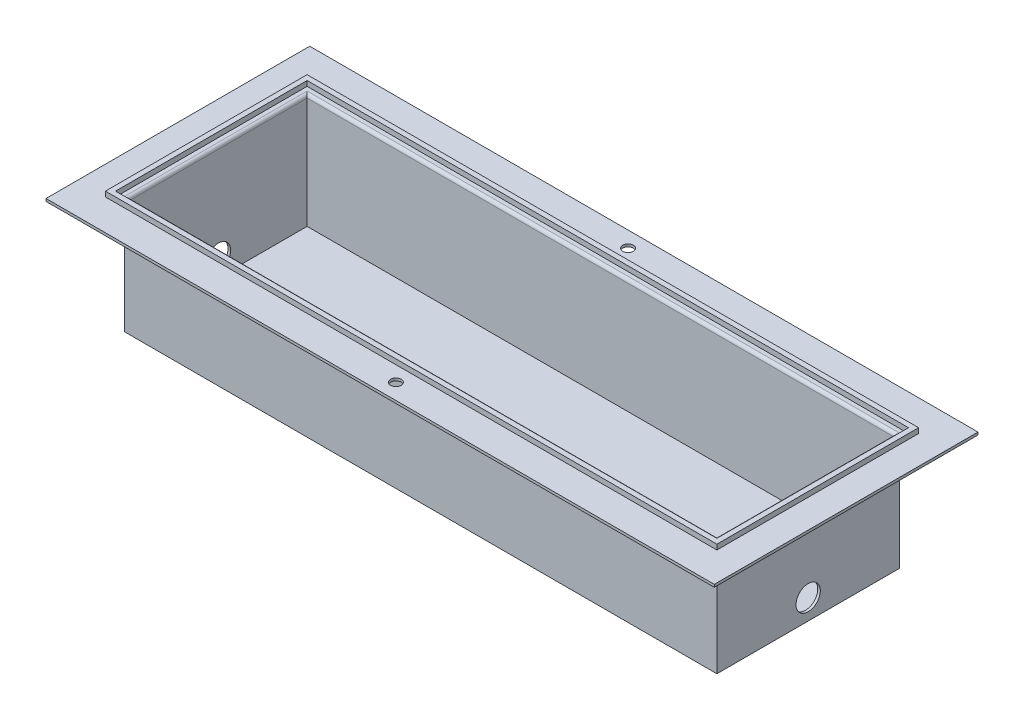
SolidWorks part; units mm, degrees
material "5052-H32"
ref_plane "Front Plane" through (0, 0, 0) normal (0, 0, 1) x (1, 0, 0)
ref_plane "Top Plane" through (0, 0, 0) normal (0, 1, 0) x (1, 0, 0)
ref_plane "Right Plane" through (0, 0, 0) normal (1, 0, 0) x (0, 0, -1)
sketch "Sketch1" plane through (0, 0, 0) normal (0, 1, 0) x (1, 0, 0)
  line L1 (185.42, 57.15) -> (-185.42, 57.15)
  line L2 (185.42, 57.15) -> (185.42, -57.15)
  line L3 (185.42, -57.15) -> (-185.42, -57.15)
  line L4 (-185.42, 57.15) -> (-185.42, -57.15)
  line L5 (185.42, 57.15) -> (-185.42, -57.15) construction
  line L6 (185.42, -57.15) -> (-185.42, 57.15) construction
  point P0 (0, 0)
  dimension "D1" = 114.3
  dimension "D2" = 370.84
extrude "Boss-Extrude1" add sketch "Sketch1" along normal blind 1.6256
sketch "Sketch2" plane through (0, 1.6256, 0) normal (0, 1, 0) x (1, 0, 0)
  line L0 (-185.42, -57.15) -> (-183.7944, -57.15) construction
  line L1 (-185.42, -57.15) -> (185.42, -57.15) construction
  line L3 (185.42, 57.15) -> (-185.42, 57.15) construction
  line L4 (185.42, -57.15) -> (185.42, -55.5244) construction
  line L5 (185.42, -57.15) -> (185.42, 57.15) construction
  line L6 (183.7944, 55.5244) -> (-183.7944, 55.5244)
  line L7 (-185.42, 57.15) -> (-183.7944, 57.15)
  line L8 (183.7944, 55.5244) -> (183.7944, -55.5244)
  line L9 (185.42, -57.15) -> (-185.42, -57.15)
  line L10 (185.42, -57.15) -> (185.42, 57.15)
  line L11 (185.42, 57.15) -> (-185.42, 57.15)
  line L12 (-185.42, -57.15) -> (-185.42, 57.15)
  line L13 (185.42, -57.15) -> (-185.42, 57.15) construction
  line L14 (185.42, 57.15) -> (-185.42, -57.15) construction
  line L15 (183.7944, -55.5244) -> (-183.7944, -55.5244)
  line L16 (-183.7944, 55.5244) -> (-183.7944, -55.5244)
  line L17 (183.7944, 55.5244) -> (-183.7944, -55.5244) construction
  line L18 (183.7944, -55.5244) -> (-183.7944, 55.5244) construction
  point P15 (0, 0)
  point P17 (0, 0)
  line M7 (-185.42, 57.15) -> (-185.42, -57.15)
  line M8 (-185.42, -57.15) -> (185.42, -57.15)
  line M9 (185.42, -57.15) -> (185.42, 57.15)
  line M10 (185.42, 57.15) -> (-185.42, 57.15)
  dimension "D1" = 1.6256
  dimension "D2" = 1.6256
extrude "Boss-Extrude2" add sketch "Sketch2" along normal blind 69.85 contours L16 L6 L8 L15 M10 M7 M8 M9
sketch "Sketch3" plane through (0, 71.4756, 0) normal (0, 1, 0) x (1, 0, 0)
  line L0 (185.42, 57.15) -> (-185.42, 57.15) construction
  line L1 (183.7944, 55.5244) -> (-183.7944, 55.5244)
  line L2 (183.7944, 55.5244) -> (183.7944, -55.5244)
  line L3 (183.7944, -55.5244) -> (-183.7944, -55.5244)
  line L4 (-183.7944, 55.5244) -> (-183.7944, -55.5244)
  line L5 (183.7944, 55.5244) -> (-183.7944, -55.5244) construction
  line L6 (183.7944, -55.5244) -> (-183.7944, 55.5244) construction
  line L7 (209.1944, 82.55) -> (-209.1944, 82.55)
  line L8 (209.1944, 82.55) -> (209.1944, -82.55)
  line L9 (209.1944, -82.55) -> (-209.1944, -82.55)
  line L10 (-209.1944, 82.55) -> (-209.1944, -82.55)
  line L11 (209.1944, 82.55) -> (-209.1944, -82.55) construction
  line L12 (209.1944, -82.55) -> (-209.1944, 82.55) construction
  point P0 (0, 0)
  point P7 (0, 0)
  dimension "D1" = 25.4
  dimension "D2" = 25.4
extrude "Boss-Extrude3" add sketch "Sketch3" along normal blind 1.6256
fillet "Fillet1" radius 1.905 8 edges at (0, 71.4756, 57.15) (185.42, 71.4756, 0) (0, 71.4756, -57.15) (-185.42, 71.4756, 0) (-183.7944, 73.1012, 0) (0, 73.1012, -55.5244) (183.7944, 73.1012, 0) (0, 73.1012, 55.5244)
sketch "Sketch6" plane through (0, 73.1012, 0) normal (0, 1, 0) x (1, 0, 0)
  line L0 (185.6994, -57.4294) -> (-185.6994, -57.4294) construction
  line L1 (188.2394, -59.9694) -> (-188.2394, -59.9694)
  line L3 (188.2394, -63.1444) -> (-188.2394, -63.1444)
  line L5 (188.2394, -59.9694) -> (-188.2394, -63.1444) construction
  line L6 (188.2394, -63.1444) -> (-188.2394, -59.9694) construction
  line L8 (0, 0) -> (-45.7363, 0) construction
  line L9 (-191.4144, 63.1444) -> (-188.2394, 63.1444)
  line L10 (-191.4144, 63.1444) -> (-191.4144, -63.1444)
  line L11 (-191.4144, -63.1444) -> (-188.2394, -63.1444)
  line L12 (-188.2394, 59.9694) -> (-188.2394, -59.9694)
  line L13 (-191.4144, 63.1444) -> (-189.8269, 0) construction
  line L14 (-191.4144, -63.1444) -> (-189.8269, 0) construction
  line L15 (-45.7363, 0) -> (27.0509, 0) construction
  line L18 (188.2394, 63.1444) -> (-188.2394, 63.1444)
  line L19 (188.2394, 59.9694) -> (-188.2394, 59.9694)
  line L20 (185.6994, 57.4294) -> (185.6994, -57.4294) construction
  line L21 (191.4144, 63.1444) -> (188.2394, 63.1444)
  line L22 (191.4144, 63.1444) -> (191.4144, -63.1444)
  line L23 (191.4144, -63.1444) -> (188.2394, -63.1444)
  line L24 (188.2394, 59.9694) -> (188.2394, -59.9694)
  line L25 (191.4144, 63.1444) -> (189.8269, 0) construction
  line L26 (191.4144, -63.1444) -> (189.8269, 0) construction
  point P0 (0, -61.5569)
  point P9 (-189.8269, 0)
  point P23 (189.8269, 0)
  dimension "D1" = 3.175
  dimension "D2" = 2.54
  dimension "D3" = 3.175
  dimension "D6" = 3.175
  dimension "D7" = 2.54
extrude "Boss-Extrude4" add sketch "Sketch6" along normal blind 3.175 contours L3 L11 L10 L9 L18 L21 L22 L23 | L1 L12 L19 L24
sketch "Sketch7" plane through (0, 73.1012, 0) normal (0, 1, 0) x (1, 0, 0)
  line L0 (0, 63.1444) -> (0, 72.6761) construction
  line L1 (-191.4144, 63.1444) -> (191.4144, 63.1444) construction
  line L2 (0, 0) -> (-34.8236, 0) construction
  circle A0 centre (0, 72.6761) radius 3.325
  circle A1 centre (0, -72.6761) radius 3.325
  dimension "D1" = 6.65
extrude "Cut-Extrude1" cut sketch "Sketch7" against normal up to next
sketch "Sketch8" plane through (185.42, 0, 0) normal (1, 0, 0) x (0, 0, -1)
  line L0 (0, 0) -> (0, 12.7) construction
  line L1 (0, 41.9519) -> (0, -41.9519) construction
  circle A0 centre (0, 12.7) radius 7.62
  dimension "D1" = 15.24
extrude "Cut-Extrude2" cut sketch "Sketch8" against normal through all
